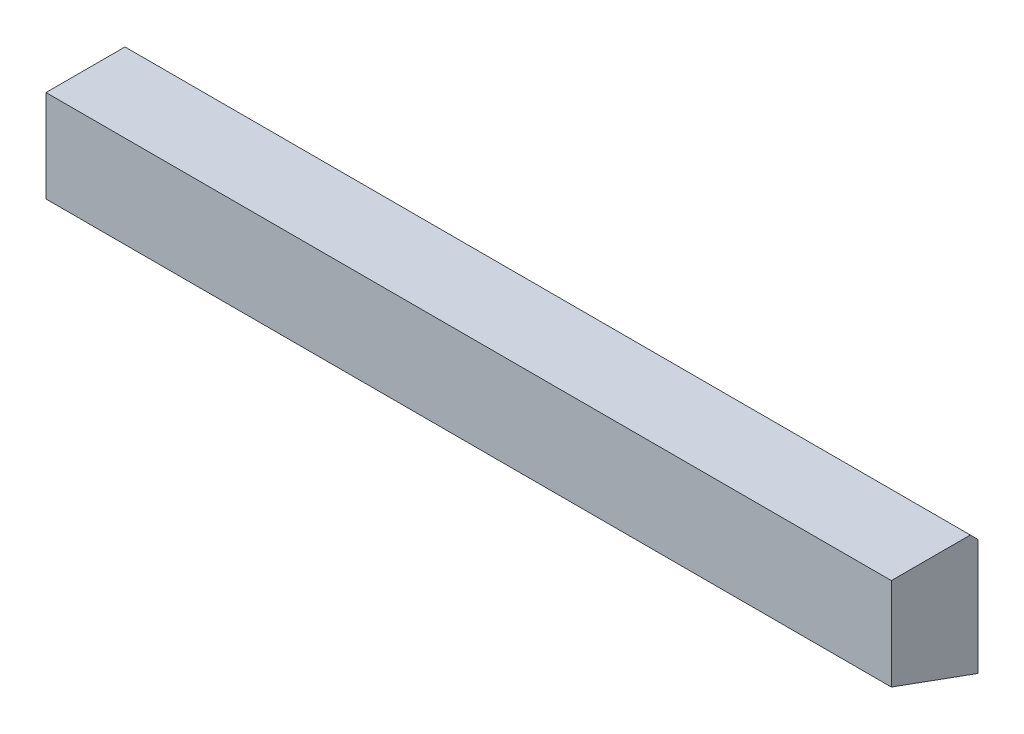
SolidWorks part; units mm, degrees
ref_plane "前视基准面" through (0, 0, 0) normal (0, 0, 1) x (1, 0, 0)
ref_plane "上视基准面" through (0, 0, 0) normal (0, 1, 0) x (1, 0, 0)
ref_plane "右视基准面" through (0, 0, 0) normal (1, 0, 0) x (0, 0, -1)
sketch "草图1" plane through (0, 0, 0) normal (1, 0, 0) x (0, 0, -1)
  line L0 (0, 6) -> (0, 0)
  line L1 (0, 0) -> (5.6382, -2.0521)
  line L2 (5.6382, -2.0521) -> (5.6382, 6)
  line L3 (5.6382, 6) -> (0, 6)
  dimension "D1" = 6
  dimension "D2" = 6
  dimension "D3" = 110
extrude "凸台-拉伸1" add sketch "草图1" along normal blind 55 contours L2 L3 L0 L1
chamfer "倒角1" distance 0.5 angle 45 1 edges at (27.5, 6, -5.6382)
